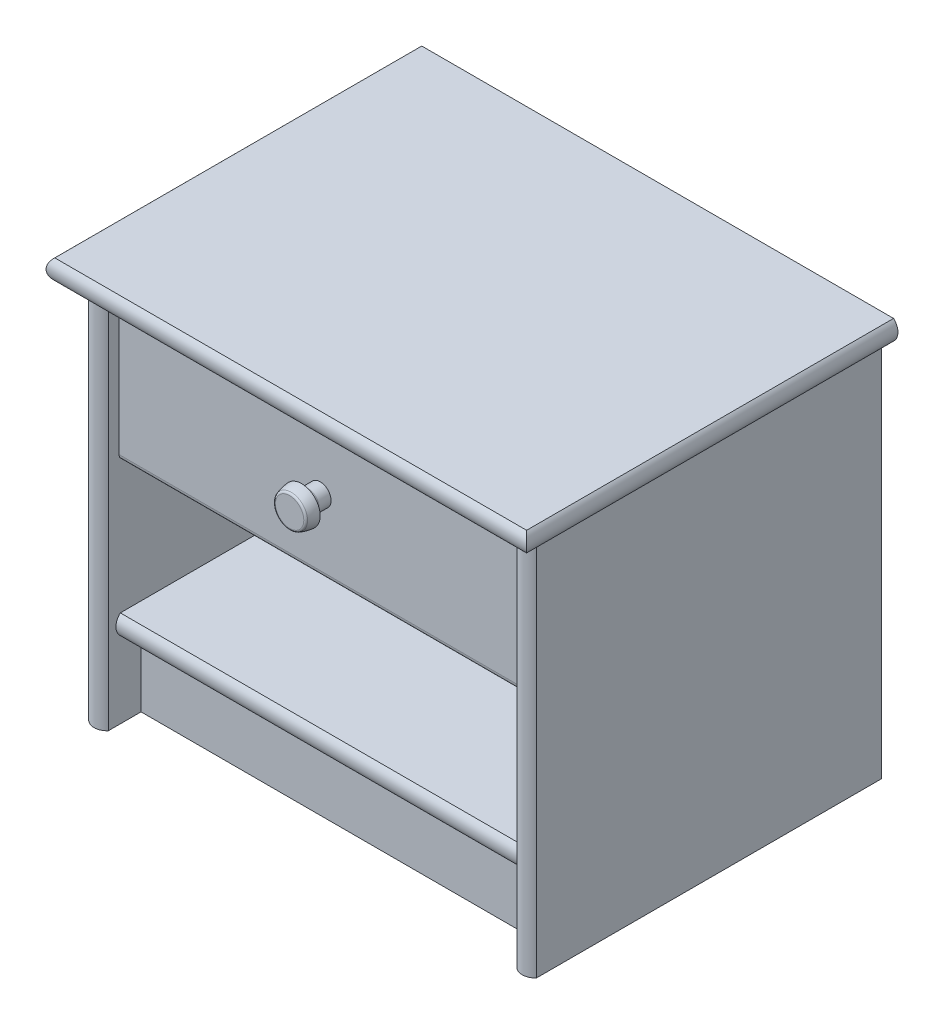
SolidWorks part; units mm, degrees
material "Chêne"
ref_plane "Plan de face" through (0, 0, 0) normal (0, 0, 1) x (1, 0, 0)
ref_plane "Plan de dessus" through (0, 0, 0) normal (0, 1, 0) x (1, 0, 0)
ref_plane "Plan de droite" through (0, 0, 0) normal (1, 0, 0) x (0, 0, -1)
sketch "Esquisse1" plane through (0, 0, 0) normal (0, 1, 0) x (1, 0, 0)
  line L0 (-205, 158) -> (205, 158)
  line L1 (205, 158) -> (205, -158)
  line L2 (205, -158) -> (187, -158) construction
  line L3 (187, -158) -> (187, -151)
  line L4 (187, -151) -> (-187, -151)
  line L5 (-187, -151) -> (-187, -158)
  line L6 (-187, -158) -> (-205, -158) construction
  line L7 (-205, -158) -> (-205, 158)
  arc A0 (-205, -158) -> (-187, -158) centre (-196, -149.875) ccw
  arc A1 (187, -158) -> (205, -158) centre (196, -149.875) ccw
  point P2 (0, 158)
  point P9 (-205, 0)
  point P12 (-196, -162)
  point P14 (196, -162)
  dimension "D1" = 410
  dimension "D2" = 18
  dimension "D3" = 7
  dimension "D4" = 4
  dimension "D5" = 320
extrude "Boss.-Extru.1" add sketch "Esquisse1" along normal mid plane 352.5
sketch "Esquisse2" plane through (-187, 0, 0) normal (1, 0, 0) x (0, 0, -1)
  line L0 (-158, 176.25) -> (-158, -176.25) construction
  line L1 (-151, -176.25) -> (-128, -176.25)
  line L2 (-158, 176.25) -> (158, 176.25) construction
  line L3 (-147, -106.25) -> (-128, -106.25)
  line L4 (-128, -176.25) -> (-128, -106.25)
  line L5 (-151, 176.25) -> (-151, -176.25) construction
  line L6 (-147, -88.25) -> (140, -88.25)
  line L7 (140, -88.25) -> (140, 36.75)
  line L8 (140, 36.75) -> (-149, 36.75)
  line L9 (158, 176.25) -> (158, -176.25) construction
  line L10 (-151, 40.75) -> (-151, -176.25)
  line L11 (-151, 176.25) -> (-148, 176.25)
  line L12 (-151, 169.25) -> (-151, 176.25)
  arc A0 (-147, -106.25) -> (-147, -88.25) centre (-138.875, -97.25) cw
  arc A1 (-149, 36.75) -> (-151, 40.75) centre (-146, 40.75) cw
  arc A2 (-151, 169.25) -> (-148, 176.25) centre (-141.3333, 169.25) cw
  line M2 (-151, -176.25) -> (-151, 176.25)
  dimension "D1" = 70
  dimension "D2" = 30
  dimension "D3" = 4
  dimension "D4" = 18
  dimension "D5" = 18
  dimension "D6" = 125
  dimension "D7" = 4
  dimension "D8" = 2
  dimension "D9" = 3
  dimension "D10" = 7
extrude "Enlèv. mat.-Extru.1" cut sketch "Esquisse2" along normal up to surface (374 mm away) contours L10 A0 L6 L7 L8 | L3 A0 L1 L4 M2 | A2 L11 M2
sketch "Esquisse3" plane through (0, 176.25, 0) normal (0, 1, 0) x (1, 0, 0)
  line L0 (-187, -151) -> (-187, -142)
  line L1 (-187, -151) -> (187, -151) construction
  line L2 (-187, -151) -> (-184, -151)
  line L3 (184, -151) -> (187, -151)
  line L4 (187, -151) -> (187, -142)
  line L5 (187, -148) -> (187, -158) construction
  line L6 (187, -148) -> (187, -151) construction
  arc A0 (-187, -142) -> (-184, -151) centre (-172, -142) ccw
  arc A1 (184, -151) -> (187, -142) centre (172, -142) ccw
  dimension "D1" = 9
  dimension "D2" = 3
extrude "Enlèv. mat.-Extru.2" cut sketch "Esquisse3" against normal up to surface (139.5 mm away) up to face at (0, 36.75, 4.5)
sketch "Esquisse4" plane through (0, 0, 0) normal (1, 0, 0) x (0, 0, -1)
  line L1 (158, 176.25) -> (-178, 176.25)
  line L2 (158, 176.25) -> (158, 194.25)
  line L3 (158, 194.25) -> (-178, 194.25)
  line L4 (-178, 176.25) -> (-178, 194.25) construction
  arc A0 (-178, 194.25) -> (-178, 176.25) centre (-169.875, 185.25) ccw
  point P6 (-182, 185.25)
  dimension "D1" = 4
  dimension "D2" = 18
  dimension "D3" = 340
extrude "Boss.-Extru.2" add sketch "Esquisse4" along normal mid plane 440
sketch "Esquisse5" plane through (0, 0, 0) normal (0, 0, 1) x (1, 0, 0)
  line L0 (220, 194.25) -> (-220, 194.25) construction
  line L1 (220, 176.25) -> (-220, 176.25) construction
  line L2 (-220, 194.25) -> (-220, 176.25) construction
  line L3 (-216, 194.25) -> (-220, 194.25)
  line L4 (-220, 194.25) -> (-220, 176.25)
  line L5 (-220, 176.25) -> (-216, 176.25)
  line L6 (220, 176.25) -> (220, 194.25) construction
  line L7 (216, 194.25) -> (220, 194.25)
  line L8 (220, 194.25) -> (220, 176.25)
  line L9 (220, 176.25) -> (216, 176.25)
  arc A0 (-216, 194.25) -> (-216, 176.25) centre (-207.875, 185.25) ccw
  arc A1 (216, 194.25) -> (216, 176.25) centre (207.875, 185.25) cw
  dimension "D1" = 4
  dimension "D2" = 4
extrude "Enlèv. mat.-Extru.3" cut sketch "Esquisse5" against normal through all and the other way through all contours L7 A1 L8 | A0 L3 L4 | A0 L4 L5 | L8 A1 L9
sketch "Esquisse6" plane through (0, 0, 0) normal (1, 0, 0) x (0, 0, -1)
  line L0 (-201.2972, 101.25) -> (-95.4269, 101.25) construction
  line L1 (158, 176.25) -> (-178, 176.25) construction
  line L2 (-151, 111.25) -> (-162, 111.25)
  line L3 (-151, 40.75) -> (-151, 169.25) construction
  line L4 (-168, 117.25) -> (-168, 118.25)
  line L5 (-168, 118.25) -> (-179, 118.25) construction
  line L6 (-168, 118.25) -> (-177.5882, 116.25) construction
  line L7 (-177.5882, 116.25) -> (-179, 114.25) construction
  line L8 (-179, 114.25) -> (-179, 101.25)
  line L9 (-151, 111.25) -> (-151, 101.25)
  line L10 (-151, 101.25) -> (-179, 101.25)
  line L11 (-179, 118.25) -> (-179, 114.25) construction
  line L12 (-179, 117.4808) -> (-168, 118.25) construction
  arc A0 (-179, 114.25) -> (-177.5882, 116.25) centre (-176.8775, 114.25) cw
  arc A1 (-177.5882, 116.25) -> (-168, 118.25) centre (-165.4772, 82.1716) cw
  arc A2 (-162, 111.25) -> (-168, 117.25) centre (-162, 117.25) cw
  point P19 (-168, 111.25)
  dimension "D9" = 6
  dimension "D1" = 75
  dimension "D2" = 10
  dimension "D3" = 17
  dimension "D4" = 11
  dimension "D5" = 13
  dimension "D6" = 15
  dimension "D7" = 17
  dimension "D8" = 4
revolve "Révolution1" add sketch "Esquisse6" angle 360 about L0
